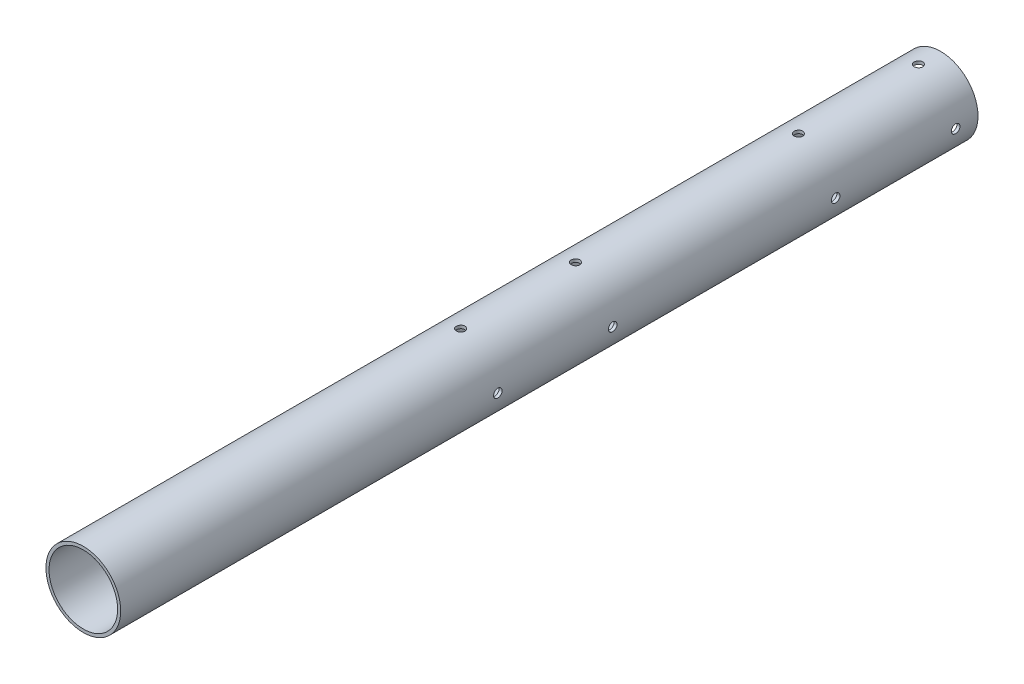
SolidWorks part; units mm, degrees
ref_plane "Front Plane" through (0, 0, 0) normal (1, 0, 0) x (0, 1, 0)
ref_plane "Top Plane" through (0, 0, 0) normal (0, 0, 1) x (0, 1, 0)
ref_plane "Right Plane" through (0, 0, 0) normal (0, 1, 0) x (-1, 0, 0)
sketch "Sketch2" plane through (0, 0, 0) normal (0, 0, 1) x (0, 1, 0)
  circle A0 centre (0, 0) radius 27.686
  circle A2 centre (0, 0) radius 25.4
  dimension "D1" = 55.372
  dimension "D2" = 50.8
extrude "tube_extrude" add sketch "Sketch2" along normal blind 635
ref_plane "bolthole_plane" through (-27.686, 0, 0) normal (-1, 0, 0) x (0, 0, 1)
sketch "Sketch4" plane through (-27.686, 0, 0) normal (-1, 0, 0) x (0, 0, 1)
  line L0 (0, 0) -> (635, 0) construction
  line L1 (635, -25.4) -> (635, 25.4) construction
  circle A0 centre (355.6, 0) radius 3.175
  circle A1 centre (270.51, 0) radius 3.175
  circle A2 centre (105.41, 0) radius 3.175
  circle A3 centre (16.51, 0) radius 3.175
  dimension "D1" = 6.35
  dimension "D3" = 6.35
  dimension "D6" = 6.35
  dimension "D7" = 6.35
  dimension "D2" = 279.4
  dimension "D4" = 85.09
  dimension "D5" = 165.1
  dimension "D8" = 88.9
extrude "boltholes" cut sketch "Sketch4" against normal up to next
pattern_circular "CirPattern2" count 4 over 360 about axis through (0, 0, 635) along (0, 0, -1) of "boltholes"
